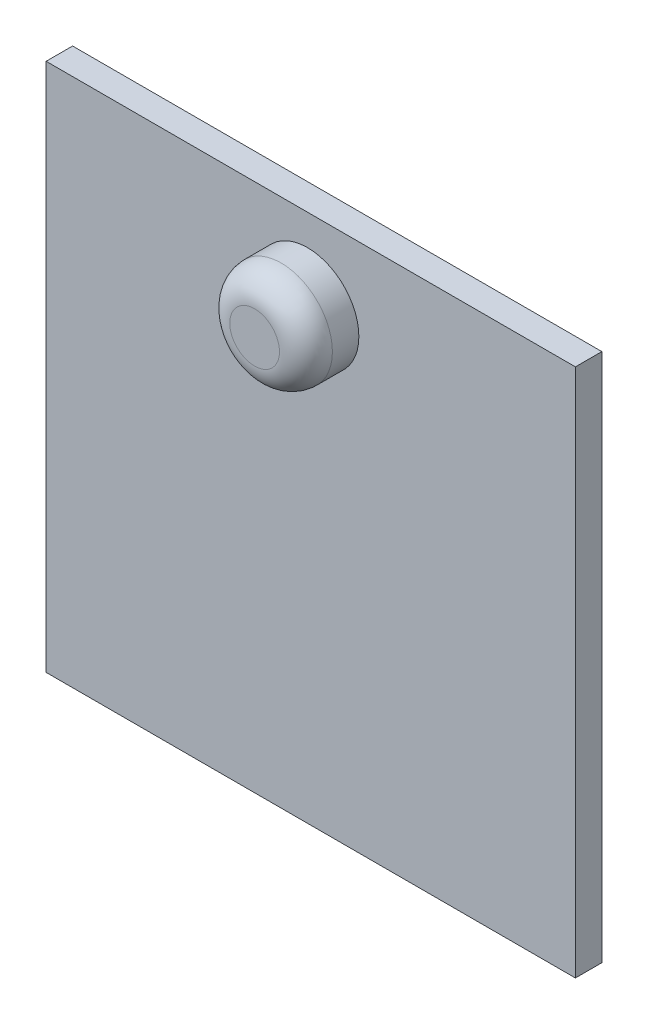
SolidWorks part; units mm, degrees
ref_plane "Front Plane" through (0, 0, 0) normal (0, 0, 1) x (1, 0, 0)
ref_plane "Top Plane" through (0, 0, 0) normal (0, 1, 0) x (1, 0, 0)
ref_plane "Right Plane" through (0, 0, 0) normal (1, 0, 0) x (0, 0, -1)
sketch "Sketch1" plane through (0, 0, 0) normal (0, 0, 1) x (1, 0, 0)
  line L1 (-55.4688, 136.7188) -> (144.5312, 136.7188)
  line L2 (-55.4688, 136.7188) -> (-55.4688, -63.2813)
  line L3 (-55.4688, -63.2813) -> (144.5313, -63.2813)
  line L4 (144.5312, 136.7188) -> (144.5313, -63.2813)
  dimension "D1" = 200
  dimension "D2" = 200
extrude "Boss-Extrude1" add sketch "Sketch1" along normal blind 10
ref_plane "Plane1" through (0, 0, 10) normal (0, 0, 1) x (1, 0, 0)
sketch "Sketch2" plane through (0, 0, 10) normal (0, 0, 1) x (1, 0, 0)
  circle A0 centre (43.3204, 105.7376) radius 19.3858
  point P2 (43.3204, 105.7376)
extrude "Boss-Extrude2" add sketch "Sketch2" along normal blind 20
fillet "Fillet1" radius 10 1 edges at (62.7062, 105.7376, 30)
